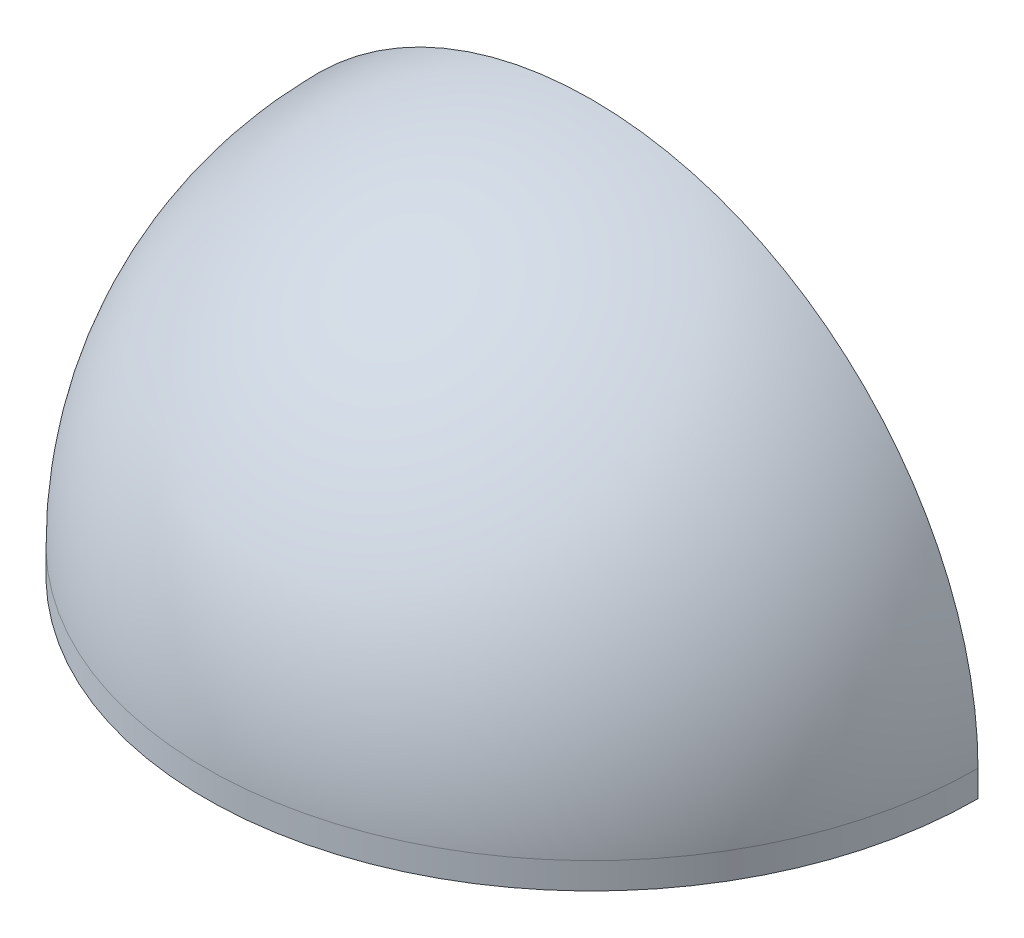
SolidWorks part; units mm, degrees
ref_plane "Alzado" through (0, 0, 0) normal (0, 0, 1) x (1, 0, 0)
ref_plane "Planta" through (0, 0, 0) normal (0, 1, 0) x (1, 0, 0)
ref_plane "Vista lateral" through (0, 0, 0) normal (1, 0, 0) x (0, 0, -1)
sketch "Croquis1" plane through (0, 0, 0) normal (0, 0, 1) x (1, 0, 0)
  line L0 (-49.7822, -2.3826) -> (-32.7149, -2.3826)
  line L1 (-29.2822, 18.1174) -> (-29.2822, 19.6174)
  line L2 (-32.7149, -12.3826) -> (-31.0822, -12.3826)
  line L3 (-32.7149, -2.3826) -> (-32.7149, -12.3826)
  line L4 (-51.2822, -2.3826) -> (-51.2822, -3.8826)
  line L5 (-31.0822, -12.3826) -> (-31.0822, -17.3826)
  line L6 (-51.2822, -3.8826) -> (-41.2822, -3.8826)
  line L7 (-41.2822, -3.8826) -> (-38.2822, -3.8826)
  line L8 (-38.2822, -3.8826) -> (-37.2822, -3.8826)
  line L9 (-37.2822, -3.8826) -> (-37.2822, -12.3826)
  line L10 (-37.2822, -12.3826) -> (-34.2822, -12.3826)
  line L11 (-34.2822, -12.3826) -> (-31.0822, -17.3826)
  arc A0 (-29.2822, 18.1174) -> (-49.7822, -2.3826) centre (-29.2822, -2.3826) ccw
  arc A1 (-51.2822, -2.3826) -> (-29.2822, 19.6174) centre (-29.2822, -2.3826) cw
revolve "Revolución1" add sketch "Croquis1" angle 180 about L1
sketch "Croquis2" plane through (0, 0, 0) normal (0, 0, -1) x (-1, 0, 0)
  line L0 (33.7149, -8.3826) -> (35.7149, -8.3826)
  line L1 (33.7149, -4.3826) -> (35.7149, -4.3826)
  line L2 (33.7149, -4.3826) -> (33.7149, -7.3826)
  line L3 (33.7149, -7.3826) -> (35.7149, -7.3826)
  line L4 (35.7149, -4.3826) -> (35.7149, -7.3826)
  line L5 (33.7149, -8.3826) -> (33.7149, -11.3826)
  line L6 (33.7149, -11.3826) -> (35.7149, -11.3826)
  line L7 (35.7149, -8.3826) -> (35.7149, -11.3826)
  line L8 (32.7149, -12.3826) -> (32.7149, -2.3826) construction
  line L9 (32.7149, -2.3826) -> (49.7822, -2.3826) construction
  line L10 (22.8494, -8.3826) -> (24.8494, -8.3826)
  line L11 (22.8494, -4.3826) -> (24.8494, -4.3826)
  line L12 (22.8494, -4.3826) -> (22.8494, -7.3826)
  line L13 (22.8494, -7.3826) -> (24.8494, -7.3826)
  line L14 (24.8494, -4.3826) -> (24.8494, -7.3826)
  line L15 (22.8494, -8.3826) -> (22.8494, -11.3826)
  line L16 (22.8494, -11.3826) -> (24.8494, -11.3826)
  line L17 (24.8494, -8.3826) -> (24.8494, -11.3826)
  line L18 (25.8494, -2.3826) -> (8.7822, -2.3826) construction
  line L19 (25.8494, -12.3826) -> (25.8494, -2.3826) construction
  dimension "D1" = 1
  dimension "D2" = 1
  dimension "D3" = 1
  dimension "D4" = 2
  dimension "D5" = 3
  dimension "D6" = 3
  dimension "D7" = 2
  dimension "D8" = 1
  dimension "D9" = 3
  dimension "D10" = 1
  dimension "D11" = 1
  dimension "D12" = 2
extrude "Cortar-Extruir1" cut sketch "Croquis2" against normal blind 20
sketch "Croquis3" plane through (-33.7149, 0, 0) normal (-1, 0, 0) x (0, 0, 1)
  line L0 (6.6596, -7.3826) -> (4.6596, -7.3826)
  line L2 (6.6596, -7.3826) -> (0, -7.3826) construction
  line L3 (4.6596, -7.3826) -> (4.6596, -4.3826)
  line L4 (6.6596, -4.3826) -> (0, -4.3826) construction
  line L5 (4.6596, -4.3826) -> (9.6596, -4.3826)
  line L6 (9.6596, -4.3826) -> (9.6596, -7.3826)
  line L7 (9.6596, -7.3826) -> (6.6596, -7.3826)
  line L8 (6.6596, -11.3826) -> (4.6596, -11.3826)
  line L9 (6.6596, -11.3826) -> (0, -11.3826) construction
  line L10 (4.6596, -11.3826) -> (4.6596, -8.3826)
  line L11 (6.6596, -8.3826) -> (0, -8.3826) construction
  line L12 (4.6596, -8.3826) -> (9.6596, -8.3826)
  line L13 (9.6596, -8.3826) -> (9.6596, -11.3826)
  line L14 (9.6596, -11.3826) -> (6.6596, -11.3826)
extrude "Cortar-Extruir2" cut sketch "Croquis3" against normal up to vertex (8.8655 mm away)
